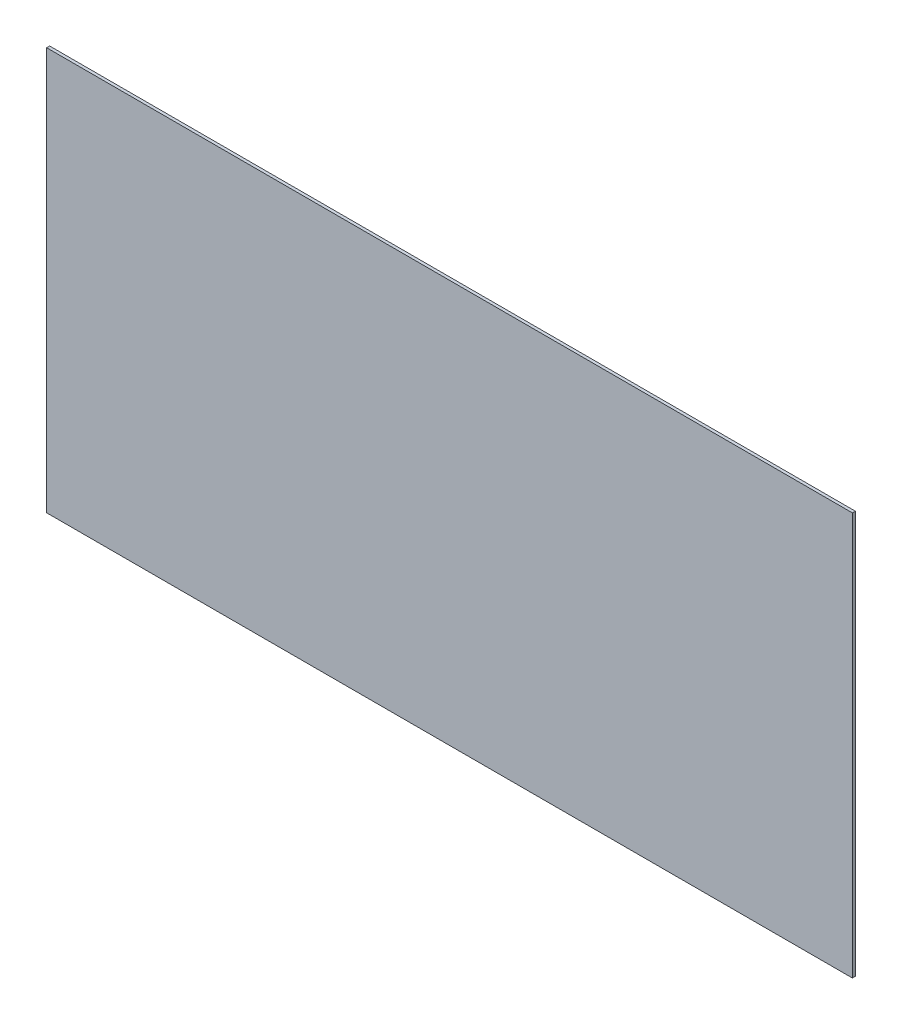
SolidWorks part; units mm, degrees
ref_plane "Front Plane" through (0, 0, 0) normal (0, 0, 1) x (1, 0, 0)
ref_plane "Top Plane" through (0, 0, 0) normal (0, 1, 0) x (1, 0, 0)
ref_plane "Right Plane" through (0, 0, 0) normal (1, 0, 0) x (0, 0, -1)
sketch "Sketch1" plane through (0, 0, 0) normal (0, 0, 1) x (1, 0, 0)
  line L1 (29, 5) -> (49, 5)
  line L2 (29, 5) -> (29, -5)
  line L3 (29, -5) -> (49, -5)
  line L4 (49, 5) -> (49, -5)
extrude "Boss-Extrude1" add sketch "Sketch1" along normal blind 0.0737
